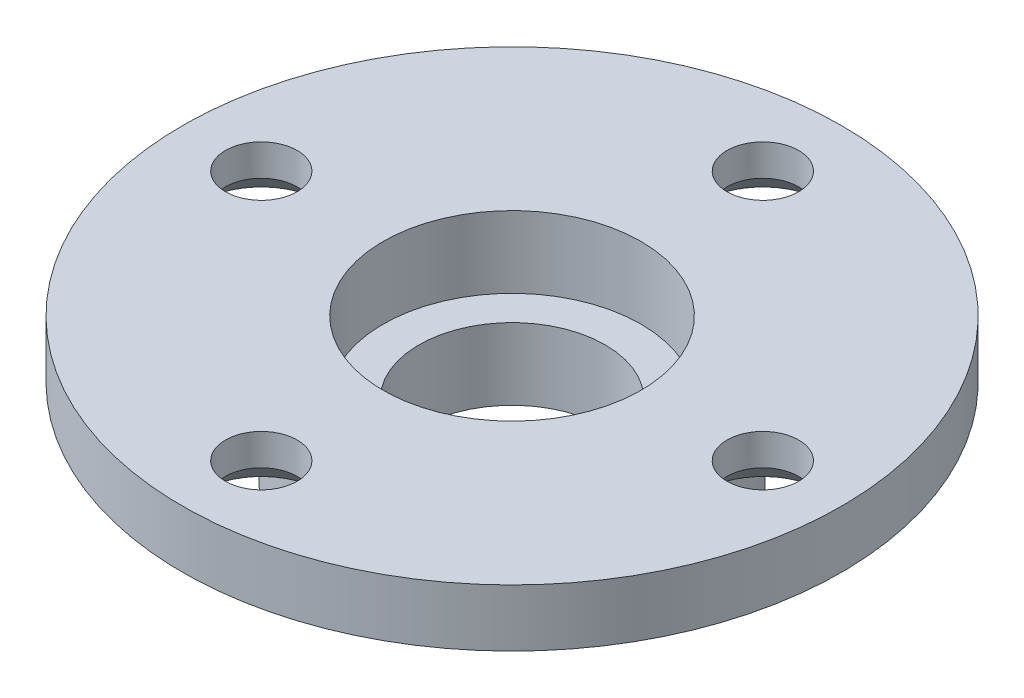
SolidWorks part; units mm, degrees
ref_plane "Piano frontale" through (0, 0, 0) normal (0, 0, 1) x (1, 0, 0)
ref_plane "Piano superiore" through (0, 0, 0) normal (0, 1, 0) x (1, 0, 0)
ref_plane "Piano destro" through (0, 0, 0) normal (1, 0, 0) x (0, 0, -1)
sketch "Schizzo1" plane through (0, 0, 0) normal (0, 0, 1) x (1, 0, 0)
  line L0 (0, 0) -> (0, 15.2969) construction
  line L1 (6.5, 0) -> (12.5, 0)
  line L2 (12.5, 0) -> (12.5, 6)
  line L3 (12.5, 6) -> (23, 6)
  line L4 (23, 6) -> (23, 10)
  line L5 (23, 10) -> (9, 10)
  line L6 (9, 10) -> (9, 5)
  line L7 (9, 5) -> (6.5, 5)
  line L8 (6.5, 5) -> (6.5, 0)
  dimension "D1" = 13
  dimension "D2" = 18
  dimension "D3" = 25
  dimension "D4" = 46
  dimension "D5" = 5
  dimension "D6" = 5
  dimension "D7" = 4
revolve "Rivoluzione1" add sketch "Schizzo1" angle 360 about L0
hole_wizard "Foro Ø5.0 (5)-1" positions "Schizzo2" profile "Schizzo3" hole size "Ø5.0" standard "ISO" end condition through all
sketch "Schizzo2" plane through (0, 10, 0) normal (0, 1, 0) x (1, 0, 0)
  line L0 (0, 0) -> (17.5, 0) construction
  point P0 (17.5, 0)
  dimension "D1" = 17.5
sketch "Schizzo3" plane through (17.5, 10, 0) normal (1, 0, 0) x (0, 0, 1)
  line L0 (0, 0) -> (0, 10)
  line L1 (0, 10) -> (2.5, 10)
  line L2 (2.5, 10) -> (2.5, 0)
  line L5 (2.5, 0) -> (0, 0)
  line L11 (0, -6.35) -> (0, 107.95) construction
  dimension "Thru Hole Dia." = 5
  dimension "Thru Hole Depth" = 10
chamfer "Smusso1" distance 1.8 angle 45 1 edges at (17.5, 6, -2.5)
pattern_circular "RipetizioneCircolare1" count 4 over 360 about axis through (0, 0, 0) along (0, 1, 0) of "Foro Ø5.0 (5)-1", "Smusso1"
